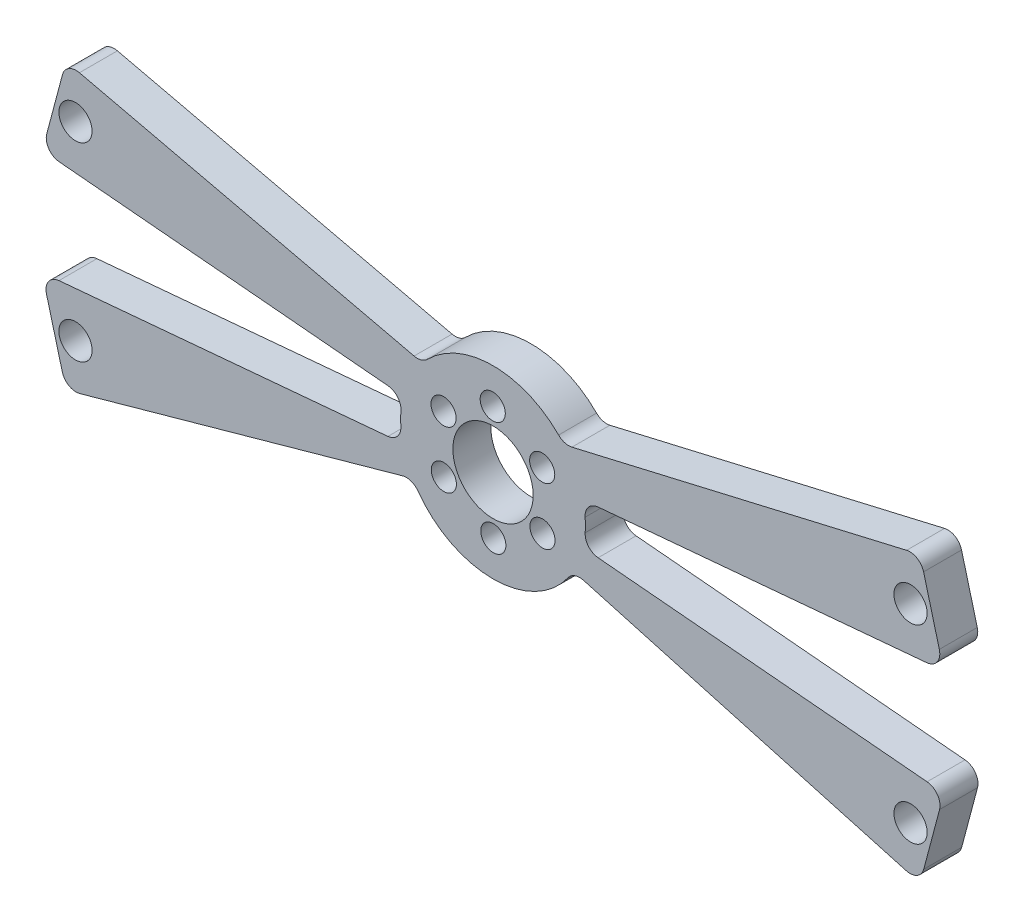
SolidWorks part; units mm, degrees
ref_plane "前视基准面" through (0, 0, 0) normal (0, 0, 1) x (1, 0, 0)
ref_plane "上视基准面" through (0, 0, 0) normal (0, 1, 0) x (1, 0, 0)
ref_plane "右视基准面" through (0, 0, 0) normal (1, 0, 0) x (0, 0, -1)
other "Configuration Table"
sketch "草图1" plane through (0, 0, 0) normal (0, 0, 1) x (1, 0, 0)
  line L24 (-44.2718, 12.9002) -> (-114.8041, 29.3396)
  line L25 (-118.3844, 27.1883) -> (-121.7019, 14.703)
  line L26 (-119.0708, 10.9447) -> (-49.7708, 4.7219)
  line L27 (-49.7848, -4.5305) -> (-119.1208, -10.7565)
  line L28 (-121.7519, -14.5148) -> (-118.4176, -27.0637)
  line L29 (-114.7111, -29.1827) -> (-46.7133, -10.1908)
  line L30 (-8.5614, -10.1908) -> (59.4364, -29.1827)
  line L31 (63.1428, -27.0637) -> (66.4772, -14.5148)
  line L32 (63.8461, -10.7565) -> (-5.4899, -4.5305)
  line L33 (-5.5039, 4.7219) -> (63.7961, 10.9447)
  line L34 (66.4271, 14.703) -> (63.1097, 27.1883)
  line L35 (59.5293, 29.3396) -> (-11.0029, 12.9002)
  arc A40 (-114.8041, 29.3396) -> (-118.3844, 27.1883) centre (-115.485, 26.4179) ccw
  arc A41 (-121.7019, 14.703) -> (-119.0708, 10.9447) centre (-118.8025, 13.9326) ccw
  arc A42 (-47.0481, 1.5024) -> (-49.7708, 4.7219) centre (-50.0391, 1.7339) ccw
  arc A43 (-47.0481, 1.5024) -> (-47.0602, -1.3365) centre (-27.6374, 0) ccw
  arc A44 (-49.7848, -4.5305) -> (-47.0602, -1.3365) centre (-50.0531, -1.5425) ccw
  arc A45 (-119.1208, -10.7565) -> (-121.7519, -14.5148) centre (-118.8525, -13.7444) ccw
  arc A46 (-118.4176, -27.0637) -> (-114.7111, -29.1827) centre (-115.5182, -26.2933) ccw
  arc A47 (-43.467, -11.3337) -> (-46.7133, -10.1908) centre (-45.9063, -13.0802) ccw
  arc A48 (-43.467, -11.3337) -> (-11.8077, -11.3337) centre (-27.6374, 0) ccw
  arc A49 (-8.5614, -10.1908) -> (-11.8077, -11.3337) centre (-9.3684, -13.0802) ccw
  arc A50 (59.4364, -29.1827) -> (63.1428, -27.0637) centre (60.2434, -26.2933) ccw
  arc A51 (66.4772, -14.5148) -> (63.8461, -10.7565) centre (63.5778, -13.7444) ccw
  arc A52 (-8.2145, -1.3365) -> (-5.4899, -4.5305) centre (-5.2216, -1.5425) ccw
  arc A53 (-8.2145, -1.3365) -> (-8.2267, 1.5024) centre (-27.6374, 0) ccw
  arc A54 (-5.5039, 4.7219) -> (-8.2267, 1.5024) centre (-5.2356, 1.7339) ccw
  arc A55 (63.7961, 10.9447) -> (66.4271, 14.703) centre (63.5277, 13.9326) ccw
  arc A56 (63.1097, 27.1883) -> (59.5293, 29.3396) centre (60.2103, 26.4179) ccw
  arc A57 (-13.8139, 13.7093) -> (-11.0029, 12.9002) centre (-11.6839, 15.8218) ccw
  arc A58 (-13.8139, 13.7093) -> (-41.4608, 13.7093) centre (-27.6374, 0) ccw
  arc A59 (-44.2718, 12.9002) -> (-41.4608, 13.7093) centre (-43.5909, 15.8218) ccw
  dimension "D1" = 3
  dimension "D2" = 19.4688
  dimension "D3" = 59.4364
  dimension "D4" = 59.5293
  dimension "D5" = 60.2103
  dimension "D6" = 60.2434
  dimension "D7" = 63.1097
  dimension "D8" = 63.5277
  dimension "D9" = 63.5778
  dimension "D10" = 63.7961
  dimension "D11" = 5.2216
  dimension "D12" = 5.2356
  dimension "D13" = 8.2145
extrude "凸台-拉伸2" add sketch "草图1" along normal blind 8 contours A59 L24 A40 L25 A41 L26 A42 A43 A44 L27 A45 L28 A46 L29 A47 A48 A49 L30 A50 L31 A51 L32 A52 A53 A54 L33 A55 L34 A56 L35 A57 A58
sketch "草图4" plane through (0, 0, 8) normal (0, 0, 1) x (1, 0, 0)
  circle A2 centre (-115.6374, -20) radius 3.5
  circle A3 centre (-115.6374, 20) radius 3.5
  circle A19 centre (60.3626, -20) radius 3.5
  circle A20 centre (60.3626, 20) radius 3.5
  arc A21 (-37.9849, -8.7035) -> (-38.0122, -3.4036) centre (-37.9986, -6.0535) ccw
  arc A22 (-38.0122, -3.4036) -> (-37.9849, -8.7035) centre (-37.9986, -6.0535) ccw
  arc A23 (-25.2737, -13.313) -> (-29.8772, -10.6867) centre (-27.5755, -11.9998) ccw
  arc A24 (-29.8772, -10.6867) -> (-25.2737, -13.313) centre (-27.5755, -11.9998) ccw
  arc A25 (-19.5023, -7.2831) -> (-14.9261, -4.6095) centre (-17.2142, -5.9463) ccw
  arc A26 (-14.9261, -4.6095) -> (-19.5023, -7.2831) centre (-17.2142, -5.9463) ccw
  circle A27 centre (-27.6374, 0) radius 8.4629
  arc A28 (-17.2625, 3.4036) -> (-17.2898, 8.7035) centre (-17.2761, 6.0535) ccw
  arc A29 (-17.2898, 8.7035) -> (-17.2625, 3.4036) centre (-17.2761, 6.0535) ccw
  arc A30 (-25.3975, 10.6867) -> (-30.001, 13.313) centre (-27.6992, 11.9998) ccw
  arc A31 (-30.001, 13.313) -> (-25.3975, 10.6867) centre (-27.6992, 11.9998) ccw
  arc A32 (-35.7724, 7.2831) -> (-40.3486, 4.6095) centre (-38.0605, 5.9463) ccw
  arc A33 (-40.3486, 4.6095) -> (-35.7724, 7.2831) centre (-38.0605, 5.9463) ccw
extrude "切除-拉伸1" cut sketch "草图4" against normal through all
